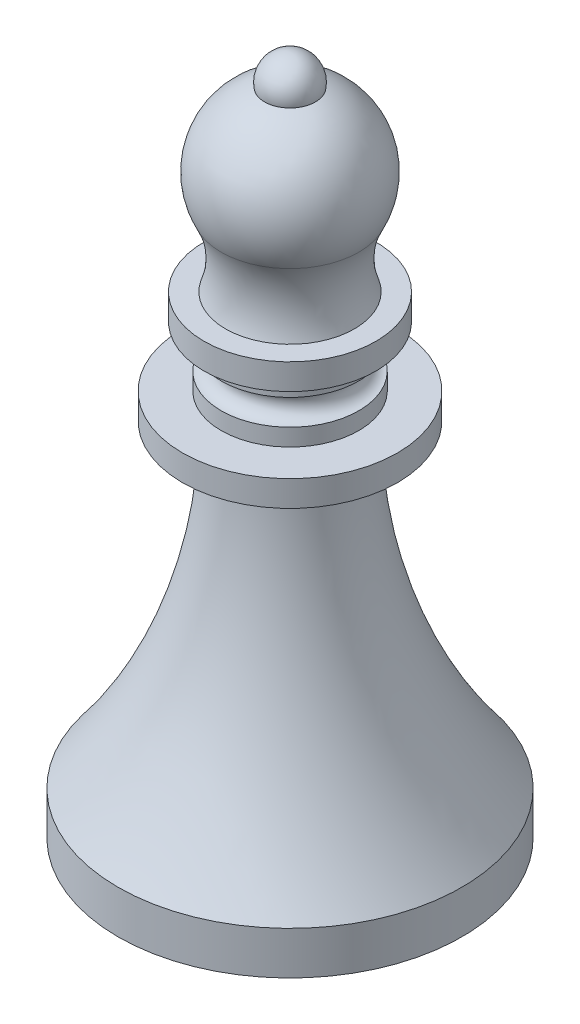
SolidWorks part; units mm, degrees
ref_plane "Front Plane" through (0, 0, 0) normal (0, 0, 1) x (1, 0, 0)
ref_plane "Top Plane" through (0, 0, 0) normal (0, 1, 0) x (1, 0, 0)
ref_plane "Right Plane" through (0, 0, 0) normal (1, 0, 0) x (0, 0, -1)
sketch "Sketch1" plane through (0, 0, 0) normal (0, 0, 1) x (1, 0, 0)
  line L0 (0, 46.4303) -> (0, -53.4276) construction
  line L1 (0, -42) -> (0, 37.0911)
  line L2 (20, -37) -> (20, -42)
  line L3 (20, -42) -> (0, -42)
  line L4 (7.5, 0) -> (12.5, 0)
  line L5 (12.5, 0) -> (12.5, 3)
  line L6 (12.5, 3) -> (8, 3)
  line L7 (8, 3) -> (8, 5)
  line L9 (8, 8) -> (8, 10)
  line L10 (8, 10) -> (10, 10)
  line L11 (10, 10) -> (10, 13)
  line L12 (10, 13) -> (7.5, 13)
  arc A0 (8, 8) -> (8, 5) centre (8, 6.5) ccw
  arc A1 (8.0056, 20.9789) -> (2.958, 33.5911) centre (0, 25.0911) ccw
  arc A2 (2.958, 33.5911) -> (0, 37.0911) centre (0, 34.0911) ccw
  arc A3 (8.0056, 20.9789) -> (7.5, 13) centre (16.9007, 16.4098) ccw
  arc A4 (7.5, 0) -> (20, -37) centre (67.499, -0.3415) ccw
  point P16 (7.5, 0)
  point P19 (7.5, 13)
  dimension "D12" = 18
  dimension "D13" = 6
  dimension "D14" = 10
  dimension "D15" = 60
  dimension "D2" = 20
  dimension "D3" = 5
  dimension "D4" = 3
  dimension "D6" = 3
  dimension "D7" = 3
  dimension "D8" = 2
  dimension "D9" = 10
  dimension "D10" = 8
  dimension "D11" = 7.5
revolve "Revolve1" add sketch "Sketch1" angle 360 about L0
fillet "Fillet1" radius 2 1 edges at (0, 0, 7.5)
scale "缩放比例1" scale about origin uniform scaling yes scale factor 0.6
